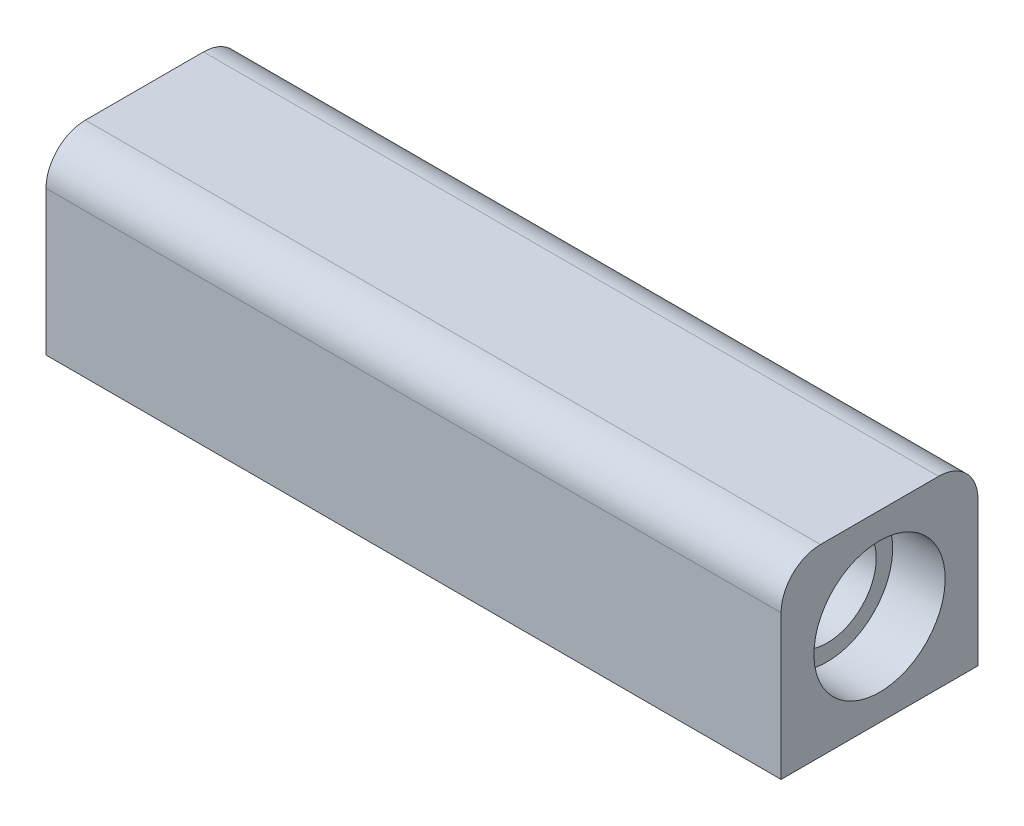
SolidWorks part; units mm, degrees
material "PVC 0.007 Plasticized"
ref_plane "Front Plane" through (0, 0, 0) normal (0, 0, 1) x (1, 0, 0)
ref_plane "Top Plane" through (0, 0, 0) normal (0, 1, 0) x (1, 0, 0)
ref_plane "Right Plane" through (0, 0, 0) normal (1, 0, 0) x (0, 0, -1)
sketch "Sketch1" plane through (0, 0, 0) normal (0, 0, 1) x (1, 0, 0)
  line L1 (28, 7) -> (-28, 7)
  line L2 (28, 7) -> (28, -7)
  line L3 (28, -7) -> (-28, -7)
  line L4 (-28, 7) -> (-28, -7)
  line L5 (28, 7) -> (-28, -7) construction
  line L6 (28, -7) -> (-28, 7) construction
  point P0 (0, 0)
  dimension "D1" = 56
  dimension "D2" = 14
extrude "Boss-Extrude1" add sketch "Sketch1" along normal blind 15
hole_wizard "Ø3.0 (3) Diameter Hole1" positions "Sketch3" profile "Sketch4" hole size "Ø3.0" standard "ISO" end condition through all
sketch "Sketch3" plane through (28, 0, 0) normal (1, 0, 0) x (0, 0, -1)
  line L0 (-15, 7) -> (0, -7) construction
  line L1 (-15, 7) -> (0, 7) construction
  line L2 (-15, -7) -> (-15, 7) construction
  point P0 (-7.5, 0)
sketch "Sketch4" plane through (28, 0, 7.5) normal (0, 1, 0) x (0, 0, -1)
  line L0 (0, 0) -> (0, 56)
  line L1 (0, 56) -> (3.75, 56)
  line L2 (3.75, 56) -> (3.75, 0)
  line L5 (3.75, 0) -> (0, 0)
  line L11 (0, -6.35) -> (0, 107.95) construction
  dimension "Thru Hole Dia." = 7.5
  dimension "Thru Hole Depth" = 56
sketch "Sketch5" plane through (28, 0, 0) normal (1, 0, 0) x (0, 0, -1)
  circle A0 centre (-7.5, 0) radius 5
  dimension "D1" = 10
extrude "Cut-Extrude1" cut sketch "Sketch5" against normal blind 4
sketch "Sketch6" plane through (-28, 0, 0) normal (-1, 0, 0) x (0, 0, 1)
  circle A0 centre (7.5, 0) radius 5
  dimension "D1" = 10
extrude "Cut-Extrude2" cut sketch "Sketch6" against normal blind 4
fillet "Fillet1" radius 3 2 edges at (0, 7, 0) (0, 7, 15)
